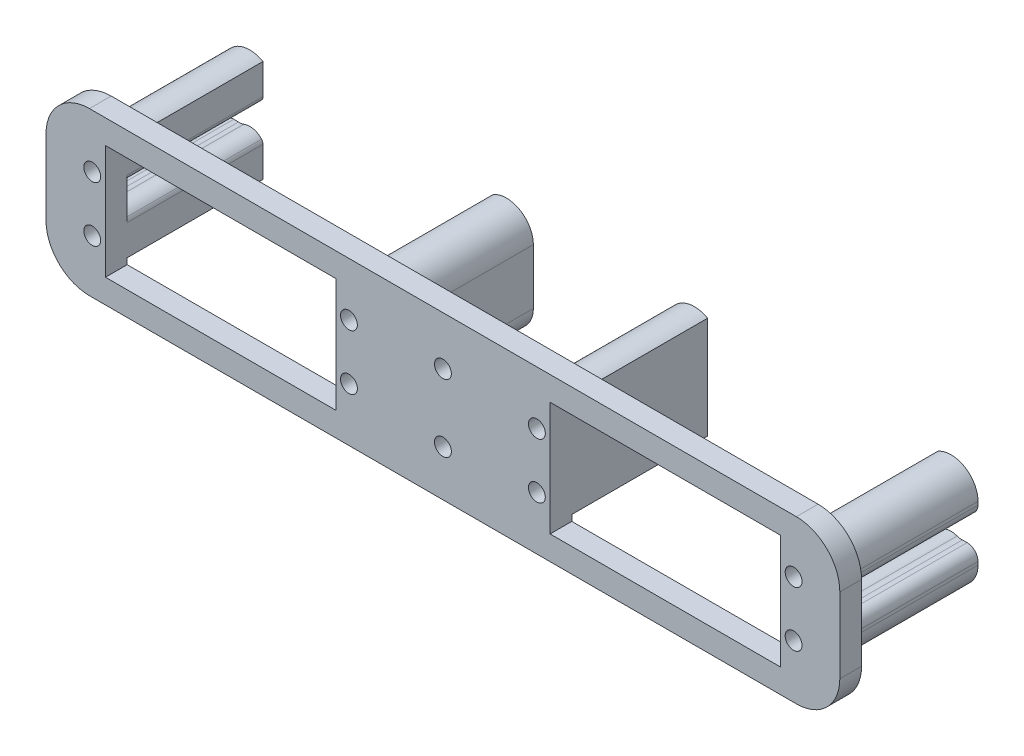
SolidWorks part; units mm, degrees
material "PET"
ref_plane "Front Plane" through (0, 0, 0) normal (0, 0, 1) x (1, 0, 0)
ref_plane "Top Plane" through (0, 0, 0) normal (0, 1, 0) x (1, 0, 0)
ref_plane "Right Plane" through (0, 0, 0) normal (1, 0, 0) x (0, 0, -1)
ref_plane "Plane1" through (0, 0, 29.721) normal (0, 0, 1) x (1, 0, 0)
sketch "Sketch1" plane through (0, 0, 29.721) normal (0, 0, 1) x (1, 0, 0)
  line L0 (114, 7.158) -> (114, 37)
  line L1 (114, 37) -> (-32.1427, 37)
  line L2 (-32.1427, 37) -> (-32.1427, 7.158)
  line L3 (-32.1427, 7.158) -> (114, 7.158)
extrude "Boss-Extrude1" add sketch "Sketch1" against normal blind 4
sketch "Sketch2" plane through (0, 0, 29.721) normal (0, 0, 1) x (1, 0, 0)
  line L0 (-21.2, 11.579) -> (21.2, 11.579)
  line L1 (21.2, 11.579) -> (21.2, 32.579)
  line L2 (21.2, 32.579) -> (-21.2, 32.579)
  line L3 (-21.2, 32.579) -> (-21.2, 11.579)
extrude "Cut-Extrude1" cut sketch "Sketch2" against normal through all
sketch "Sketch3" plane through (0, 0, 25.721) normal (0, 0, -1) x (-1, 0, 0)
  line L0 (-103.0573, 11.579) -> (-60.6573, 11.579)
  line L1 (-60.6573, 11.579) -> (-60.6573, 32.579)
  line L2 (-60.6573, 32.579) -> (-103.0573, 32.579)
  line L3 (-103.0573, 32.579) -> (-103.0573, 11.579)
extrude "Cut-Extrude2" cut sketch "Sketch3" against normal through all
sketch "Sketch4" plane through (0, 0, 25.721) normal (0, 0, -1) x (-1, 0, 0)
  line L0 (28.58, 27.164) -> (28.58, 24.579)
  line L1 (28.58, 24.579) -> (25.7, 24.579)
  line L2 (21.2, 25.5269) -> (21.2, 31.4765)
  arc A0 (21.2, 31.4765) -> (28.58, 27.164) centre (23.63, 27.164) cw
  arc A1 (25.7, 24.579) -> (24.7259, 24.4467) centre (25.4739, 22.5918) ccw
  arc A2 (24.7259, 24.4467) -> (21.2, 25.5269) centre (23.63, 27.164) cw
extrude "Boss-Extrude2" add sketch "Sketch4" along normal blind 25
sketch "Sketch5" plane through (0, 0, 25.721) normal (0, 0, -1) x (-1, 0, 0)
  line L0 (25.7, 19.579) -> (28.58, 19.579)
  line L1 (28.58, 19.579) -> (28.58, 16.994)
  line L2 (21.2, 12.6815) -> (21.2, 18.6311)
  arc A0 (24.7259, 19.7114) -> (25.7, 19.579) centre (25.4739, 21.5662) ccw
  arc A1 (28.58, 16.994) -> (21.2, 12.6815) centre (23.63, 16.994) cw
  arc A2 (21.2, 18.6311) -> (24.7259, 19.7114) centre (23.63, 16.994) cw
extrude "Boss-Extrude3" add sketch "Sketch5" along normal blind 25
sketch "Sketch6" plane through (0, 0, 25.721) normal (0, 0, -1) x (-1, 0, 0)
  line L0 (-107.5573, 24.579) -> (-110.4373, 24.579)
  line L1 (-110.4373, 24.579) -> (-110.4373, 27.164)
  line L2 (-103.0573, 31.4765) -> (-103.0573, 25.5269)
  arc A0 (-106.5832, 24.4467) -> (-107.5573, 24.579) centre (-107.3312, 22.5918) ccw
  arc A1 (-110.4373, 27.164) -> (-103.0573, 31.4765) centre (-105.4873, 27.164) cw
  arc A2 (-103.0573, 25.5269) -> (-106.5832, 24.4467) centre (-105.4873, 27.164) cw
extrude "Boss-Extrude4" add sketch "Sketch6" along normal blind 25
sketch "Sketch7" plane through (0, 0, 25.721) normal (0, 0, -1) x (-1, 0, 0)
  line L0 (-110.4373, 16.994) -> (-110.4373, 19.579)
  line L1 (-110.4373, 19.579) -> (-107.5573, 19.579)
  line L2 (-103.0573, 18.6311) -> (-103.0573, 12.6815)
  arc A0 (-103.0573, 12.6815) -> (-110.4373, 16.994) centre (-105.4873, 16.994) cw
  arc A1 (-107.5573, 19.579) -> (-106.5832, 19.7114) centre (-107.3312, 21.5662) ccw
  arc A2 (-106.5832, 19.7114) -> (-103.0573, 18.6311) centre (-105.4873, 16.994) cw
extrude "Boss-Extrude5" add sketch "Sketch7" along normal blind 25
sketch "Sketch8" plane through (0, 0, 25.721) normal (0, 0, -1) x (-1, 0, 0)
  line L0 (-28.58, 16.994) -> (-28.58, 27.164)
  line L1 (-21.2, 31.4765) -> (-21.2, 12.6815)
  arc A0 (-28.58, 27.164) -> (-21.2, 31.4765) centre (-23.63, 27.164) cw
  arc A1 (-21.2, 12.6815) -> (-28.58, 16.994) centre (-23.63, 16.994) cw
extrude "Boss-Extrude6" add sketch "Sketch8" along normal blind 25
sketch "Sketch9" plane through (0, 0, 25.721) normal (0, 0, -1) x (-1, 0, 0)
  line L0 (-53.2773, 27.164) -> (-53.2773, 16.994)
  line L1 (-60.6573, 12.6815) -> (-60.6573, 31.4765)
  arc A0 (-53.2773, 16.994) -> (-60.6573, 12.6815) centre (-58.2273, 16.994) cw
  arc A1 (-60.6573, 31.4765) -> (-53.2773, 27.164) centre (-58.2273, 27.164) cw
extrude "Boss-Extrude7" add sketch "Sketch9" along normal blind 25
hole_wizard "Ø3.1 (3.1) Diameter Hole1" positions "Sketch11" profile "Sketch10" hole size "Ø3.1" standard "ANSI Metric"
sketch "Sketch11" plane through (0, 0, 29.721) normal (0, 0, 1) x (1, 0, 0)
  point P0 (40.9286, 15.6185)
  point P1 (40.9286, 28.0395)
sketch "Sketch10" plane through (40.9286, 15.6185, 29.721) normal (1, 0, 0) x (0, -1, 0)
  line L0 (0, 0) -> (0, 29)
  line L1 (0, 29) -> (1.55, 29)
  line L2 (1.55, 29) -> (1.55, 0)
  line L5 (1.55, 0) -> (0, 0)
  line L11 (0, -6.35) -> (0, 107.95) construction
  dimension "Thru Hole Dia." = 3.1
  dimension "Thru Hole Depth" = 29
hole_wizard "Ø3.1 (3.1) Diameter Hole2" positions "Sketch13" profile "Sketch12" hole size "Ø3.1" standard "ANSI Metric"
sketch "Sketch13" plane through (0, 0, 29.721) normal (0, 0, 1) x (1, 0, 0)
  point P0 (-23.63, 27.164)
  point P1 (-23.63, 16.994)
  point P2 (23.63, 16.994)
  point P3 (23.63, 27.164)
  point P4 (58.2273, 16.994)
  point P5 (58.2273, 27.164)
  point P6 (105.4873, 16.994)
  point P7 (105.4873, 27.164)
sketch "Sketch12" plane through (-23.63, 27.164, 29.721) normal (1, 0, 0) x (0, -1, 0)
  line L0 (0, 0) -> (0, 29)
  line L1 (0, 29) -> (1.55, 29)
  line L2 (1.55, 29) -> (1.55, 0)
  line L5 (1.55, 0) -> (0, 0)
  line L11 (0, -6.35) -> (0, 107.95) construction
  dimension "Thru Hole Dia." = 3.1
  dimension "Thru Hole Depth" = 29
fillet "Fillet1" radius 1 4 edges at (-21.2, 25.5269, 13.221) (103.0573, 18.6311, 13.221) (103.0573, 25.5269, 13.221) (-21.2, 18.6311, 13.221)
fillet "Fillet2" radius 2 4 edges at (110.4373, 19.579, 13.221) (110.4373, 24.579, 13.221) (-28.58, 24.579, 13.221) (-28.58, 19.579, 13.221)
fillet "Fillet3" radius 8 4 edges at (-32.1427, 37, 27.721) (-32.1427, 7.158, 27.721) (114, 37, 27.721) (114, 7.158, 27.721)
